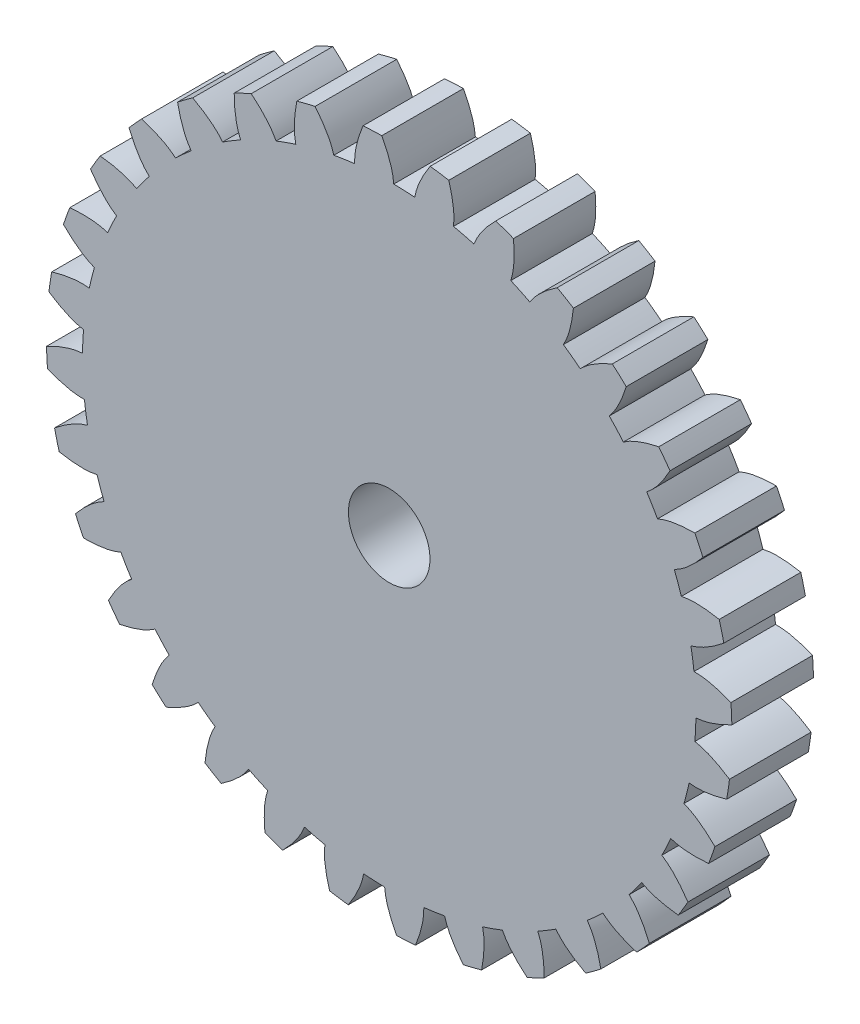
SolidWorks part; units mm, degrees
ref_plane "Front Plane" through (0, 0, 0) normal (0, 0, 1) x (1, 0, 0)
ref_plane "Top Plane" through (0, 0, 0) normal (0, 1, 0) x (1, 0, 0)
ref_plane "Right Plane" through (0, 0, 0) normal (1, 0, 0) x (0, 0, -1)
sketch "punti involuta" plane through (0, 0, 0) normal (0, 0, 1) x (1, 0, 0)
  line L0 (0, 0) -> (0, 4.6277) construction
  line L1 (-3.4916, 4) -> (3.4916, 4) construction
  line L2 (-3.4916, 2.7292) -> (3.4916, 5.2708) construction
  line L3 (0, 0) -> (-1.2856, 3.5321) construction
  line L4 (-1.2856, 3.5321) -> (0, 4) construction
  line L5 (-1.9173, 3.233) -> (-0.1385, 4.2879) construction
  line L6 (-0.9999, 3.6233) -> (0.0297, 3.9075) construction
  circle A0 centre (0, 0) radius 4 construction
  circle A1 centre (0, 0) radius 3.7588 construction
  arc A2 (-1.2856, 3.5321) -> (-1.9173, 3.233) centre (0, 0) ccw construction
  arc A3 (-1.2856, 3.5321) -> (-0.9999, 3.6233) centre (0, 0) cw construction
  arc A4 (-1.2856, 3.5321) -> (0.056, 3.7584) centre (0, 0) cw construction
  point P4 (0, 4)
  point P7 (0, 4)
  dimension "D1" = 8
  dimension "D2" = 20
  dimension "D3" = 1.3681
  dimension "D5" = 2.0681
  dimension "D7" = 1.0681
  dimension "D4" = 0.7
  dimension "D6" = 0.3
  dimension "D8" = 1.3681
sketch "diametro testa" plane through (0, 0, 0) normal (0, 0, 1) x (1, 0, 0)
  circle A0 centre (0, 0) radius 4.25
  dimension "D1" = 8.5
sketch "profilo" plane through (0, 0, 0) normal (0, 0, 1) x (1, 0, 0)
  line L0 (0, 0) -> (-0.1844, 3.7542) construction
  line L1 (0, 0) -> (0, 4.6277) construction
  line L2 (-0.1844, 3.7542) -> (-0.2085, 4.2449)
  arc A1 (-0.2085, 4.2449) -> (-0.1168, 4.2484) centre (0, 0) cw
  circle A3 centre (0, 0) radius 4.25 construction
  arc A4 (0.056, 3.7584) -> (-0.1844, 3.7542) centre (0, 0) ccw
  arc A5 (0.056, 3.7584) -> (-1.2856, 3.5321) centre (0, 0) ccw construction
  circle A6 centre (0, 0) radius 3.7588 construction
  spline S0 degree 3 poles (-0.1385, 4.2879) (-0.0478, 4.1243) (0.0412, 3.9487) (0.056, 3.7584) knots 0 0 0 0 1 1 1 1
  dimension "D1" = 2.813
sketch "diametro base" plane through (0, 0, 0) normal (0, 0, 1) x (1, 0, 0)
  circle A0 centre (0, 0) radius 3.7588
extrude "Boss-Extrude7" add sketch "profilo" along normal blind 1 contours S0 A1 L2 A4
ref_plane "Plane1" through (0, 0, 0) normal (0.9988, 0.0491, 0) x (-0.0491, 0.9988, 0)
mirror "Mirror1" about plane through (0, 0, 0) normal (0.9988, 0.0491, 0) of bodies 112
pattern_circular "CirPattern1" count 32 over 360 of bodies 113
extrude "Boss-Extrude9" add sketch "diametro base" along normal up to surface (1 mm away)
sketch "mozzo" plane through (0, 0, 0) normal (0, 0, 1) x (1, 0, 0)
  circle A0 centre (0, 0) radius 0.5
  dimension "D1" = 1
extrude "Cut-Extrude1" cut sketch "mozzo" along normal up to surface (1 mm away) up to face at (0, 0, 1)
sketch "Sketch1" plane through (0, 0, 1) normal (0, 0, 1) x (1, 0, 0)
  circle A0 centre (0, 0) radius 4.25 construction
  circle A1 centre (0, 0) radius 4.25
  circle A2 centre (0, 0) radius 4.2
  dimension "D1" = 0.05
extrude "Cut-Extrude2" cut sketch "Sketch1" against normal through all
equation "\"n_imposto\"= 32"
equation "\"m\"= .25"
equation "\"d_imposto\"= \"n_imposto\" * \"m\""
equation "\"alpha\"= 20"
equation "\"a1\"= .7"
equation "\"a2\"= .3"
equation "\"s\"= 1"
equation "\"D1@punti involuta\"=\"d_imposto\""
equation "\"D2@punti involuta\" = \"alpha\""
equation "\"D4@punti involuta\" = \"a1\""
equation "\"D5@punti involuta\" = \"D3@punti involuta\" + \"a1\""
equation "\"D6@punti involuta\" = \"a2\""
equation "\"D7@punti involuta\" = \"D3@punti involuta\" - \"a2\""
equation "\"D1@diametro testa\"=\"d_imposto\" + \"m\" * 2"
equation "\"D8@punti involuta\"=\"D3@punti involuta\""
equation "\"D1@profilo\"=360 / \"n_imposto\" / 4"
equation "\"D1@Boss-Extrude7\"=\"s\""
equation "\"D1@CirPattern1\"= \"n_imposto\""
equation "\"d_mozzo\"= 1"
equation "\"D1@mozzo\"=\"d_mozzo\""
